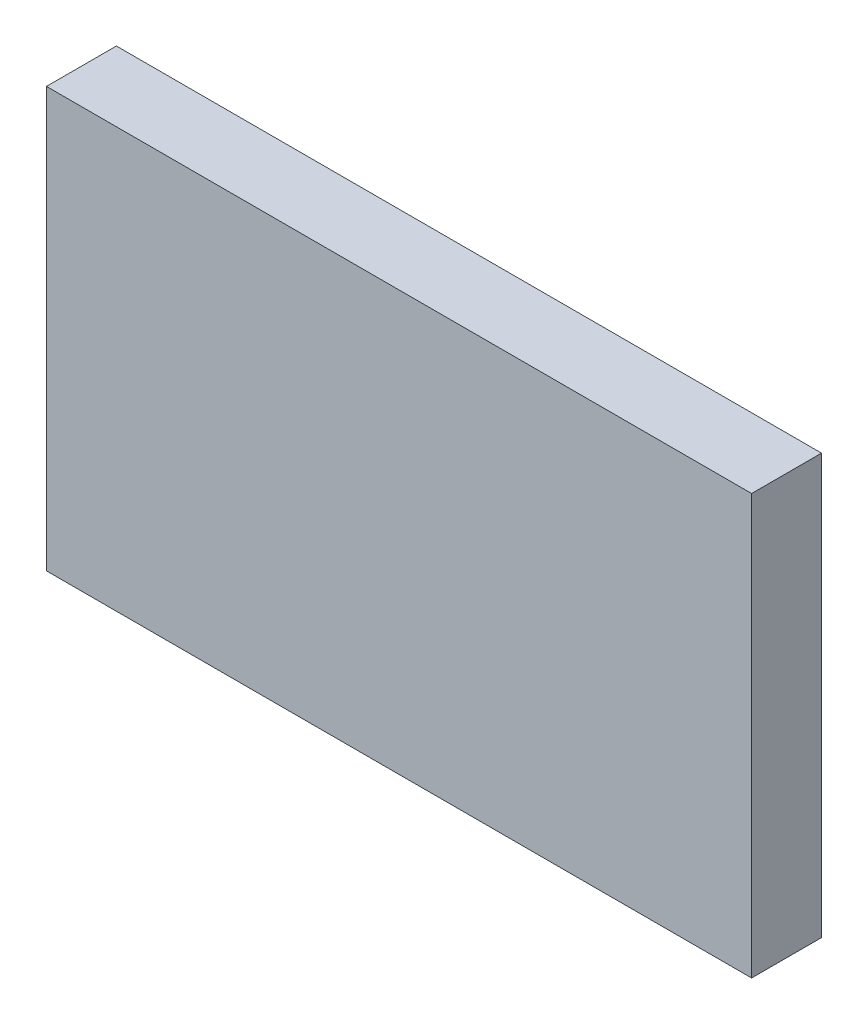
SolidWorks part; units mm, degrees
ref_plane "Front Plane" through (0, 0, 0) normal (0, 0, 1) x (1, 0, 0)
ref_plane "Top Plane" through (0, 0, 0) normal (0, 1, 0) x (1, 0, 0)
ref_plane "Right Plane" through (0, 0, 0) normal (1, 0, 0) x (0, 0, -1)
sketch "Sketch1" plane through (0, 0, 0) normal (0, 0, 1) x (1, 0, 0)
  line L1 (30.25, 18) -> (-30.25, 18)
  line L2 (30.25, 18) -> (30.25, -18)
  line L3 (30.25, -18) -> (-30.25, -18)
  line L4 (-30.25, 18) -> (-30.25, -18)
  line L5 (0, -18) -> (0, 18) construction
  line L6 (30.25, 0) -> (-30.25, 0) construction
  point P0 (0, 0)
  dimension "D1" = 60.5
  dimension "D2" = 36
extrude "Boss-Extrude1" add sketch "Sketch1" along normal blind 6
